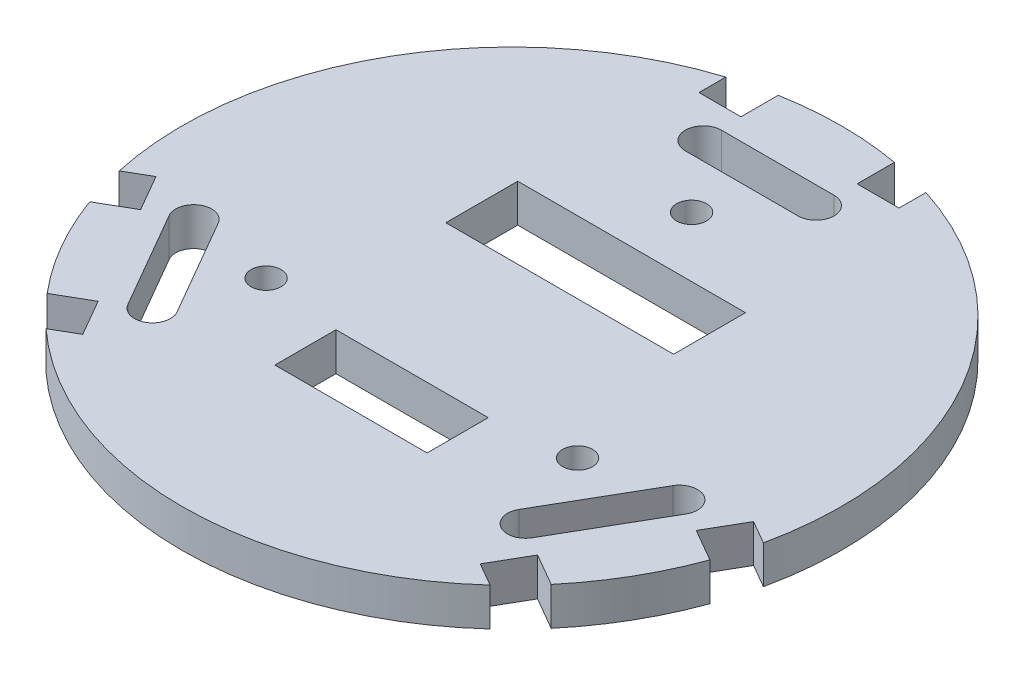
SolidWorks part; units mm, degrees
material "Acrylic (Medium-high impact)"
ref_plane "Front Plane" through (0, 0, 0) normal (0, 0, 1) x (1, 0, 0)
ref_plane "Top Plane" through (0, 0, 0) normal (0, 1, 0) x (1, 0, 0)
ref_plane "Right Plane" through (0, 0, 0) normal (1, 0, 0) x (0, 0, -1)
sketch "Sketch2" plane through (0, 0, 0) normal (0, 1, 0) x (1, 0, 0)
  circle A0 centre (0, 0) radius 27.5
  dimension "D1" = 55
extrude "Boss-Extrude1" add sketch "Sketch2" along normal blind 3.175
sketch "Sketch3" plane through (0, 3.175, 0) normal (0, 1, 0) x (1, 0, 0)
  line L0 (0, 0) -> (0, 27.5) construction
  line L1 (0, 0) -> (23.8157, -13.75) construction
  line L2 (0, 0) -> (-23.8157, -13.75) construction
  line L3 (-1.905, 23.68) -> (-1.905, 20.68)
  line L4 (-1.905, 23.68) -> (1.9049, 23.68)
  line L5 (-1.905, 20.68) -> (1.9049, 20.68)
  line L6 (1.9049, 23.68) -> (1.9049, 20.68)
  line L7 (-1.905, 23.68) -> (1.9049, 20.68) construction
  line L8 (-1.905, 20.68) -> (1.9049, 23.68) construction
  line L9 (-16.3679, -11.6499) -> (-19.6675, -13.5549)
  line L10 (-16.3679, -11.6499) -> (-18.2729, -8.3503)
  line L11 (-19.6675, -13.5549) -> (-21.5725, -10.2553)
  line L12 (-18.2729, -8.3503) -> (-21.5725, -10.2553)
  line L13 (-16.3679, -11.6499) -> (-21.5725, -10.2553) construction
  line L14 (-19.6675, -13.5549) -> (-18.2729, -8.3503) construction
  line L15 (16.3626, -11.6466) -> (19.6558, -13.5626)
  line L16 (16.3626, -11.6466) -> (18.2786, -8.3535)
  line L17 (19.6558, -13.5626) -> (21.5718, -10.2695)
  line L18 (18.2786, -8.3535) -> (21.5718, -10.2695)
  line L19 (16.3626, -11.6466) -> (21.5718, -10.2695) construction
  line L20 (19.6558, -13.5626) -> (18.2786, -8.3535) construction
  line L21 (0, 0) -> (-22.5, 6) construction
  line L22 (-21.0829, 11.3143) -> (-27.5884, 13.0491)
  line L23 (-27.5884, 13.0491) -> (-28.9935, 7.7798)
  line L24 (-23.9171, 0.6857) -> (-30.4227, 2.4205)
  line L25 (-30.4227, 2.4205) -> (-28.9935, 7.7798)
  line L26 (0, 27.5) -> (0, -27.5) construction
  line L27 (-4.7, 22.18) -> (4.7, 22.18)
  line L28 (4.7, 19.18) -> (-4.7, 19.18)
  line L29 (21.5584, -7.0197) -> (16.8584, -15.1603)
  line L30 (14.2604, -13.6603) -> (18.9604, -5.5197)
  line L31 (-16.8584, -15.1603) -> (-21.5584, -7.0197)
  line L32 (-18.9604, -5.5197) -> (-14.2604, -13.6603)
  circle A0 centre (0, 0) radius 27.5 construction
  arc A1 (-1.905, 23.68) -> (1.9049, 23.68) centre (-0.0001, 23.68) cw
  arc A2 (-1.905, 20.68) -> (1.9049, 20.68) centre (-0.0001, 20.68) ccw
  arc A3 (19.6558, -13.5626) -> (21.5718, -10.2695) centre (20.6138, -11.9161) ccw
  arc A4 (16.3626, -11.6466) -> (18.2786, -8.3535) centre (17.3206, -10) cw
  arc A5 (-16.3679, -11.6499) -> (-18.2729, -8.3503) centre (-17.3204, -10.0001) ccw
  arc A6 (-21.5725, -10.2553) -> (-19.6675, -13.5549) centre (-20.62, -11.9051) ccw
  circle A7 centre (0, 15) radius 1.25
  circle A8 centre (-12.9904, -7.5) radius 1.25
  circle A9 centre (12.9904, -7.5) radius 1.25
  arc A10 (-23.9171, 0.6857) -> (-21.0829, 11.3143) centre (-22.5, 6) ccw
  circle A11 centre (-4.7, 20.68) radius 1.5
  circle A12 centre (4.7, 20.68) radius 1.5
  circle A13 centre (20.2594, -6.2697) radius 1.5
  circle A14 centre (15.5594, -14.4103) radius 1.5
  circle A15 centre (-15.5594, -14.4103) radius 1.5
  circle A16 centre (-20.2594, -6.2697) radius 1.5
  point P9 (0, 22.18)
  point P10 (-18.9702, -10.9526)
  point P11 (18.9672, -10.958)
  point P74 (0, 0)
  dimension "D16" = 15
  dimension "D17" = 2.5
  dimension "D19" = 15
  dimension "D20" = 5.5
  dimension "D22" = 4.7
  dimension "D21" = 3
  dimension "D1" = 120
  dimension "D2" = 120
  dimension "D3" = 3
  dimension "D4" = 3
  dimension "D5" = 3.81
  dimension "D6" = 0.0001
  dimension "D7" = 3.81
  dimension "D8" = 3.81
  dimension "D9" = 20
  dimension "D10" = 0.0001
  dimension "D11" = 3.81
  dimension "D12" = 0.0127
  dimension "D13" = 3.81
  dimension "D14" = 20
  dimension "D15" = 1.905
  dimension "D18" = 15
  dimension "D23" = 0
  dimension "D24" = 20.68
extrude "Cut-Extrude1" cut sketch "Sketch3" against normal blind 3.175 contours A11 | A7 | A8 | A9 | A11 L28 A2 L3 L27 | L28 A2 L5 | L27 L3 L5 L6 | L28 A12 L27 L6 A2 | A12 | A15 | A15 L32 A5 L9 L31 | L31 L9 L10 L12 | L10 A5 L32 | L32 A16 L31 L12 A5 | A16 | A13 L30 A4 L18 L29 | L29 L18 L16 L15 | L30 A14 L29 L15 A4 | A4 L16 L30 | A14 | A13
sketch "Sketch4" plane through (0, 3.175, 0) normal (0, 1, 0) x (1, 0, 0)
  line L0 (-27.1042, -10.0542) -> (-23.1724, -7.7842)
  line L1 (-27.1042, -10.0542) -> (-28.8542, -7.0231)
  line L2 (-23.1724, -7.7842) -> (-24.9224, -4.7531)
  line L3 (-28.8542, -7.0231) -> (-24.9224, -4.7531)
  line L4 (-22.2592, -18.446) -> (-20.5092, -21.4771)
  line L6 (-22.2592, -18.446) -> (-18.3274, -16.176)
  line L7 (-20.5092, -21.4771) -> (-16.5774, -19.2071)
  line L8 (-18.3274, -16.176) -> (-16.5774, -19.2071)
  line L11 (4.8449, 28.5) -> (4.8449, 23.96)
  line L12 (4.8449, 23.96) -> (8.3449, 23.96)
  line L13 (8.3449, 28.5) -> (8.3449, 23.96)
  line L14 (4.8449, 28.5) -> (8.3449, 28.5)
  line L15 (-4.8451, 28.5) -> (-4.8451, 23.96)
  line L16 (-4.8451, 23.96) -> (-8.3451, 23.96)
  line L17 (-8.3451, 28.5) -> (-8.3451, 23.96)
  line L18 (-4.8451, 28.5) -> (-8.3451, 28.5)
  line L19 (22.2593, -18.4458) -> (18.3275, -16.1758)
  line L20 (18.3275, -16.1758) -> (16.5775, -19.2069)
  line L21 (20.5093, -21.4769) -> (16.5775, -19.2069)
  line L22 (22.2593, -18.4458) -> (20.5093, -21.4769)
  line L23 (27.1043, -10.054) -> (23.1725, -7.784)
  line L24 (23.1725, -7.784) -> (24.9225, -4.7529)
  line L25 (28.8543, -7.0229) -> (24.9225, -4.7529)
  line L26 (27.1043, -10.054) -> (28.8543, -7.0229)
  point P8 (-27.9792, -8.5387)
  point P33 (0, 0)
  dimension "D3" = 3.5
  dimension "D4" = 4.54
  dimension "D6" = 4.54
  dimension "D7" = 0
  dimension "D8" = 3.5
  dimension "D9" = 3
extrude "Cut-Extrude2" cut sketch "Sketch4" against normal blind 10
sketch "Sketch5" plane through (0, 3.175, 0) normal (0, 1, 0) x (1, 0, 0)
  line L1 (-9.5, 4) -> (9.5, 4)
  line L2 (-9.5, 4) -> (-9.5, 10)
  line L3 (-9.5, 10) -> (9.5, 10)
  line L4 (9.5, 4) -> (9.5, 10)
  line L5 (-6.35, -13.4103) -> (6.35, -13.4103)
  line L6 (-6.35, -13.4103) -> (-6.35, -8.3103)
  line L7 (-6.35, -8.3103) -> (6.35, -8.3103)
  line L8 (6.35, -13.4103) -> (6.35, -8.3103)
  circle A0 centre (0, 15) radius 1.25 construction
  dimension "D1" = 5
  dimension "D2" = 19
  dimension "D3" = 6
  dimension "D4" = 9.5
  dimension "D5" = 5.1
  dimension "D6" = 12.7
  dimension "D7" = 6.35
  dimension "D8" = 1
extrude "Cut-Extrude3" cut sketch "Sketch5" against normal blind 10
